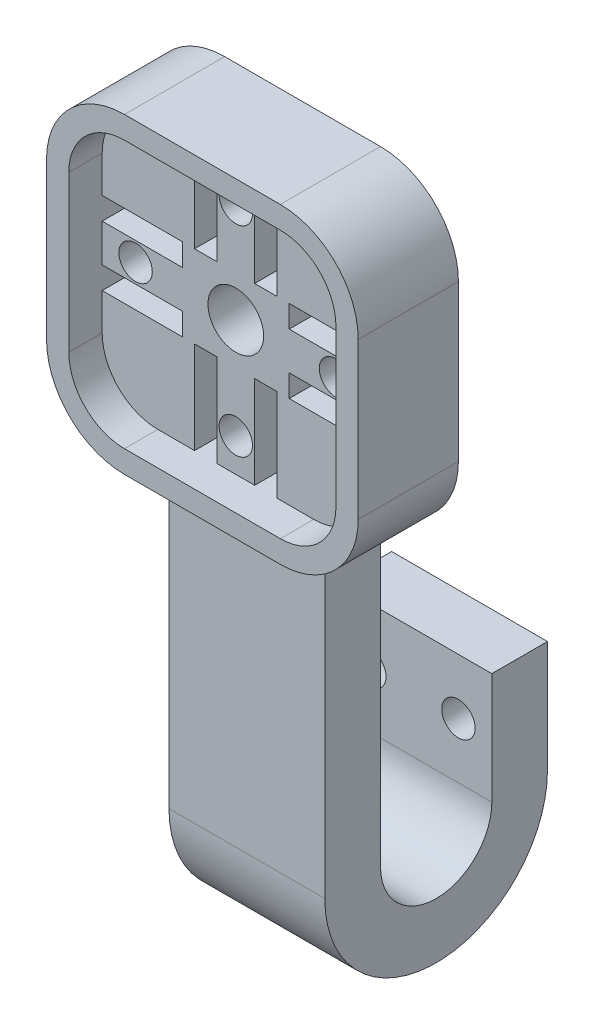
SolidWorks part; units mm, degrees
material "6063-O"
ref_plane "Ön Düzlem" through (0, 0, 0) normal (0, 0, 1) x (1, 0, 0)
ref_plane "Üst Düzlem" through (0, 0, 0) normal (0, 1, 0) x (1, 0, 0)
ref_plane "Sağ Düzlem" through (0, 0, 0) normal (1, 0, 0) x (0, 0, -1)
sketch "Çizim1" plane through (0, 0, 0) normal (0, 0, 1) x (1, 0, 0)
  line L0 (17, 7) -> (17, -7)
  line L1 (-7, 12) -> (7, 12)
  line L2 (-12, 7) -> (-12, -7)
  line L3 (-7, -12) -> (7, -12)
  line L4 (12, 7) -> (12, -7)
  line L5 (-12, 12) -> (12, -12) construction
  line L6 (-12, -12) -> (12, 12) construction
  line L7 (-7, -17) -> (7, -17)
  line L8 (-17, 7) -> (-17, -7)
  line L9 (-7, 17) -> (7, 17)
  arc A0 (-12, -7) -> (-7, -12) centre (-7, -7) ccw
  arc A1 (7, -12) -> (12, -7) centre (7, -7) ccw
  arc A2 (7, 12) -> (12, 7) centre (7, 7) cw
  arc A3 (-7, 12) -> (-12, 7) centre (-7, 7) ccw
  arc A4 (7, 17) -> (17, 7) centre (7, 7) cw
  arc A5 (7, -17) -> (17, -7) centre (7, -7) ccw
  arc A6 (-17, -7) -> (-7, -17) centre (-7, -7) ccw
  arc A7 (-7, 17) -> (-17, 7) centre (-7, 7) ccw
  point P0 (0, 0)
  dimension "D3" = 5
  dimension "D1" = 24
  dimension "D2" = 24
  dimension "D4" = 5
extrude "Yükseklik-Ekstrüzyon1" add sketch "Çizim1" along normal blind 9
sketch "Çizim2" plane through (0, 0, 0) normal (0, 0, 1) x (1, 0, 0)
  line L0 (-7, -12) -> (7, -12) construction
  line L1 (12, -7) -> (12, 7) construction
  line L2 (7, 12) -> (-7, 12) construction
  line L3 (-12, 7) -> (-12, -7) construction
  line L4 (-7, -12) -> (7, -12)
  line L5 (12, -7) -> (12, 7)
  line L6 (7, 12) -> (-7, 12)
  line L7 (-12, 7) -> (-12, -7)
  arc A0 (-12, -7) -> (-7, -12) centre (-7, -7) ccw construction
  arc A1 (7, -12) -> (12, -7) centre (7, -7) ccw construction
  arc A2 (12, 7) -> (7, 12) centre (7, 7) ccw construction
  arc A3 (-7, 12) -> (-12, 7) centre (-7, 7) ccw construction
  arc A4 (-12, -7) -> (-7, -12) centre (-7, -7) ccw
  arc A5 (7, -12) -> (12, -7) centre (7, -7) ccw
  arc A6 (12, 7) -> (7, 12) centre (7, 7) ccw
  arc A7 (-7, 12) -> (-12, 7) centre (-7, 7) ccw
extrude "Yükseklik-Ekstrüzyon2" add sketch "Çizim2" along normal blind 6
sketch "Çizim3" plane through (0, 0, 6) normal (0, 0, 1) x (1, 0, 0)
  line L0 (-3.7, 12) -> (-1.7, 12)
  line L1 (-1.7, 12) -> (-1.7, 3.7)
  line L2 (1.7, 12) -> (1.7, 3.7)
  line L3 (-3.7, 12) -> (-3.7, 3.7)
  line L4 (7, 12) -> (-7, 12) construction
  line L5 (-12, 3.7) -> (-12, 1.7)
  line L6 (-12, -1.7) -> (-12, -3.7)
  line L7 (-12, -1.7) -> (-4.8, -1.7)
  line L12 (3.7, 12) -> (3.7, 3.7)
  line L13 (-3.7, 3.7) -> (-1.7, 3.7)
  line L14 (-3.7, 12) -> (-1.7, 12)
  line L15 (1.7, 12) -> (3.7, 12)
  line L16 (3.7, 3.7) -> (1.7, 3.7)
  line L25 (3.7, -12) -> (1.7, -12)
  line L26 (1.7, -12) -> (1.7, -3.7)
  line L27 (3.7, -3.7) -> (1.7, -3.7)
  line L28 (3.7, -12) -> (3.7, -3.7)
  line L29 (-3.7, -3.7) -> (-1.7, -3.7)
  line L30 (-1.7, -12) -> (-1.7, -3.7)
  line L31 (-1.7, -12) -> (-3.7, -12)
  line L32 (-3.7, -12) -> (-3.7, -3.7)
  line L41 (-3.7, 3.7) -> (-3.7, 1.7) [skipped]
  line L42 (-12, 1.7) -> (-12, 3.7) [skipped]
  line L43 (-12, 3.7) -> (-3.7, 3.7) [skipped]
  line L44 (-12, 1.7) -> (-3.7, 1.7) [skipped]
  line L45 (-12, -1.7) -> (-3.7, -1.7) [skipped]
  line L46 (-12, -3.7) -> (-3.7, -3.7) [skipped]
  line L47 (-12, -3.7) -> (-12, -1.7) [skipped]
  line L48 (-3.7, -3.7) -> (-3.7, -1.7) [skipped]
  line L49 (3.7, -3.7) -> (3.7, -1.7) [skipped]
  line L50 (12, -1.7) -> (12, -3.7) [skipped]
  line L51 (12, -1.7) -> (3.7, -1.7) [skipped]
  line L52 (12, -3.7) -> (3.7, -3.7) [skipped]
  line L53 (12, 1.7) -> (3.7, 1.7) [skipped]
  line L54 (12, 3.7) -> (3.7, 3.7) [skipped]
  line L55 (3.7, 3.7) -> (3.7, 1.7) [skipped]
  line L56 (12, 3.7) -> (12, 1.7) [skipped]
  line L57 (-12, 1.7) -> (-4.8, 1.7)
  line L58 (-12, -3.7) -> (-4.8, -3.7)
  line L59 (-12, 3.7) -> (-4.8, 3.7)
  line L60 (-4.8, 3.7) -> (-4.8, 1.7)
  line L61 (-4.8, -1.7) -> (-4.8, -3.7)
  line L62 (4.8, 3.7) -> (4.8, 1.7)
  line L63 (12, 1.7) -> (12, 3.7)
  line L64 (12, 1.7) -> (4.8, 1.7)
  line L65 (7, 12) -> (-7, 12) construction
  line L66 (12, 3.7) -> (4.8, 3.7)
  line L67 (12, -1.7) -> (4.8, -1.7)
  line L68 (4.8, -3.7) -> (4.8, -1.7)
  line L69 (12, -3.7) -> (12, -1.7)
  line L70 (12, -3.7) -> (4.8, -3.7)
  line L71 (-12, 7) -> (-12, -7) construction
  line L73 (12, -7) -> (12, 7) construction
  point P14 (0, 12)
  point P40 (-12, 0)
  point P43 (12, 0)
  point P47 (0, 0)
  line M27 (-7, -12) -> (7, -12)
  line M29 (12, -7) -> (12, 7)
  line M31 (7, 12) -> (-7, 12)
  line M33 (-12, 7) -> (-12, -7)
  dimension "D2" = 4
  dimension "D1" = 8.3
  dimension "D3" = 2
  dimension "D8" = 7.2
  dimension "D9" = 1.7
  dimension "D10" = 1.7
  dimension "D11" = 1.7
  dimension "D12" = 1.7
  dimension "D13" = 1.7
  dimension "D14" = 1.7
  dimension "D4" = 2
  dimension "D5" = 2
  dimension "D6" = 2
  dimension "D7" = 2
sketch "Çizim4" plane through (0, 0, 6) normal (0, 0, 1) x (1, 0, 0)
  line L0 (7, 12) -> (-7, 12) construction
  circle A0 centre (0, 9) radius 1.5
  circle A1 centre (0, 0) radius 2.5
  circle A2 centre (9, 0) radius 1.5
  circle A3 centre (0, -9) radius 1.5
  circle A4 centre (-9, 0) radius 1.5
  point P14 (0, 0)
  dimension "D1" = 3
  dimension "D2" = 5
  dimension "D4" = 3
  dimension "D3" = 4
extrude "Kes-Ekstrüzyon2" cut sketch "Çizim4" against normal blind 6.5
sketch "Çizim5" plane through (0, 0, 0) normal (0, 0, 1) x (1, 0, 0)
  line L0 (-7, -17) -> (7, -17)
  line L1 (7, -17) -> (7, -32)
  line L2 (7, -32) -> (-7, -32)
  line L3 (-7, -32) -> (-7, -17)
  dimension "D1" = 15
extrude "Yükseklik-Ekstrüzyon3" add sketch "Çizim5" along normal blind 5
sketch "Çizim6" plane through (0, 0, 0) normal (1, 0, 0) x (0, 0, -1)
  line L5 (0, -32) -> (-5, -32)
  line L8 (0, -42) -> (0, -32)
  line L9 (-5, -32) -> (-5, -42)
  line L14 (15, -42) -> (15, -32)
  line L15 (15, -32) -> (10, -32)
  line L16 (10, -42) -> (10, -32)
  arc A4 (-5, -42) -> (15, -42) centre (5, -42) ccw
  arc A5 (0, -42) -> (10, -42) centre (5, -42) ccw
  dimension "D1" = 10
extrude "Yükseklik-Ekstrüzyon4" add sketch "Çizim6" along normal mid plane 14
extrude "Kes-Ekstrüzyon3" cut sketch "Çizim3" against normal blind 3 contours L66 L62 L64 M29 | L16 L12 L2 M31 | L3 L13 L1 M31 | L60 L59 L57 M33 | L61 L7 L58 M33 | L32 L30 L29 M27 | L28 L27 L26 M27 | L70 L67 L68 M29
ref_plane "Düzlem1" through (0, 0, -10) normal (0, 0, 1) x (1, 0, 0)
sketch "Çizim8" plane through (0, 0, -10) normal (0, 0, 1) x (1, 0, 0)
  line L1 (7, -32) -> (-7, -32) construction
  circle A0 centre (-4, -37) radius 1.5
  circle A1 centre (4, -37) radius 1.5
  point P6 (0, -32)
  dimension "D2" = 3
  dimension "D1" = 4
  dimension "D3" = 5
extrude "Kes-Ekstrüzyon5" cut sketch "Çizim8" against normal blind 10 contours A0 | A1
sketch "Çizim9" plane through (0, 0, 0) normal (0, 0, -1) x (-1, 0, 0)
  circle A24 centre (0, 9) radius 2.5
  circle A25 centre (0, 0) radius 4
  circle A26 centre (9, 0) radius 2.5
  circle A27 centre (0, -9) radius 2.5
  circle A28 centre (-9, 0) radius 2.5
  point P11 (0, 0)
  dimension "D1" = 5
  dimension "D2" = 8
  dimension "D3" = 4
extrude "Kes-Ekstrüzyon6" cut sketch "Çizim9" against normal blind 2
sketch "Çizim11" plane through (0, 0, -15) normal (0, 0, -1) x (-1, 0, 0)
  circle A0 centre (-4, -37) radius 2.5
  circle A1 centre (4, -37) radius 2.5
  dimension "D1" = 5
extrude "Kes-Ekstrüzyon8" cut sketch "Çizim11" against normal blind 2
sketch "Çizim12" plane through (0, 0, 9) normal (0, 0, 1) x (1, 0, 0)
  line L0 (7, 14) -> (-7, 14)
  line L1 (-14, 7) -> (-14, -7)
  line L2 (-7, -14) -> (7, -14)
  line L3 (14, -7) -> (14, 7)
  line L4 (7, 17) -> (-7, 17)
  line L5 (-17, 7) -> (-17, -7)
  line L6 (-7, -17) -> (7, -17)
  line L7 (17, -7) -> (17, 7)
  line L8 (7, 17) -> (-7, 17)
  line L9 (-17, 7) -> (-17, -7)
  line L10 (-7, -17) -> (7, -17)
  line L11 (17, -7) -> (17, 7)
  arc A0 (14, 7) -> (7, 14) centre (7, 7) ccw
  arc A1 (-7, 14) -> (-14, 7) centre (-7, 7) ccw
  arc A2 (-14, -7) -> (-7, -14) centre (-7, -7) ccw
  arc A3 (7, -14) -> (14, -7) centre (7, -7) ccw
  arc A4 (17, 7) -> (7, 17) centre (7, 7) ccw
  arc A5 (-7, 17) -> (-17, 7) centre (-7, 7) ccw
  arc A6 (-17, -7) -> (-7, -17) centre (-7, -7) ccw
  arc A7 (7, -17) -> (17, -7) centre (7, -7) ccw
  arc A8 (17, 7) -> (7, 17) centre (7, 7) ccw
  arc A9 (-7, 17) -> (-17, 7) centre (-7, 7) ccw
  arc A10 (-17, -7) -> (-7, -17) centre (-7, -7) ccw
  arc A11 (7, -17) -> (17, -7) centre (7, -7) ccw
  dimension "D1" = 0
  dimension "D2" = 3
extrude "Kes-Ekstrüzyon9" cut sketch "Çizim12" against normal blind 10
sketch "Çizim14" plane through (0, 0, 0) normal (0, 0, 1) x (1, 0, 0)
  line L0 (-7, -14) -> (-7, -17)
  line L1 (-7, -17) -> (7, -17)
  line L2 (7, -17) -> (7, -14)
  line L3 (7, -14) -> (-7, -14)
extrude "Yükseklik-Ekstrüzyon5" add sketch "Çizim14" along normal blind 5
